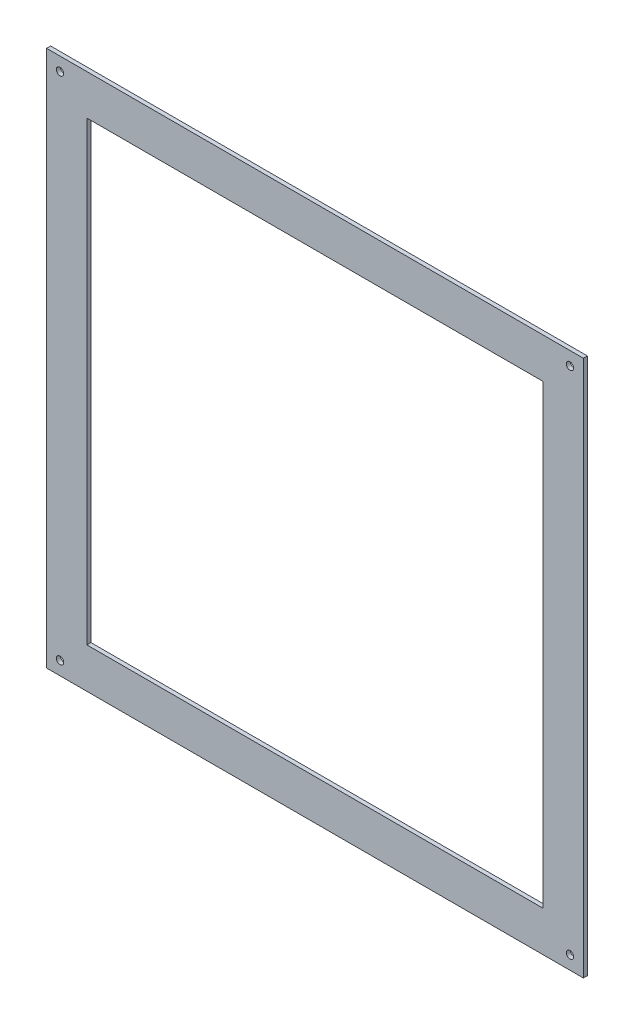
SolidWorks part; units mm, degrees
ref_plane "Plan de face" through (0, 0, 0) normal (0, 0, 1) x (1, 0, 0)
ref_plane "Plan de dessus" through (0, 0, 0) normal (0, 1, 0) x (1, 0, 0)
ref_plane "Plan de droite" through (0, 0, 0) normal (1, 0, 0) x (0, 0, -1)
sketch "Esquisse1" plane through (0, 0, 0) normal (0, 0, 1) x (1, 0, 0)
  line L1 (-200, 200) -> (200, 200)
  line L2 (-200, 200) -> (-200, -200)
  line L3 (-200, -200) -> (200, -200)
  line L4 (200, 200) -> (200, -200)
  line L5 (-200, 200) -> (200, -200) construction
  line L6 (-200, -200) -> (200, 200) construction
  line L7 (170, 170) -> (-170, 170)
  line L8 (170, 170) -> (170, -170)
  line L9 (170, -170) -> (-170, -170)
  line L10 (-170, 170) -> (-170, -170)
  line L11 (170, 170) -> (-170, -170) construction
  line L12 (170, -170) -> (-170, 170) construction
  point P0 (0, 0)
  point P6 (0, 0)
  dimension "D1" = 400
  dimension "D2" = 400
  dimension "D3" = 30
  dimension "D4" = 30
extrude "Boss.-Extru.1" add sketch "Esquisse1" along normal blind 3
hole_wizard "Dégagement M51" positions "Esquisse3" profile "Esquisse2" hole size "M5" standard "Din" end condition through all
sketch "Esquisse3" plane through (0, 0, 3) normal (0, 0, 1) x (1, 0, 0)
  line L12 (190, -190) -> (190, 190)
  line L13 (190, 190) -> (-190, 190)
  line L14 (-190, 190) -> (-190, -190)
  line L15 (-190, -190) -> (190, -190)
  line L16 (190, -190) -> (190, 190)
  line L17 (190, 190) -> (-190, 190)
  line L18 (-190, 190) -> (-190, -190)
  line L19 (-190, -190) -> (190, -190)
  point P0 (-190, -190)
  point P2 (-190, 190)
  point P4 (190, 190)
  point P6 (190, -190)
  dimension "D1" = 10
sketch "Esquisse2" plane through (-190, -190, 3) normal (1, 0, 0) x (0, -1, 0)
  line L0 (0, 0) -> (0, 3)
  line L1 (0, 3) -> (2.75, 3)
  line L2 (2.75, 3) -> (2.75, 0)
  line L5 (2.75, 0) -> (0, 0)
  line L11 (0, -6.35) -> (0, 107.95) construction
  dimension "Diamètre du perçage jusqu'au prochain" = 5.5
  dimension "Profondeur du perçage jusqu'au prochain" = 3
